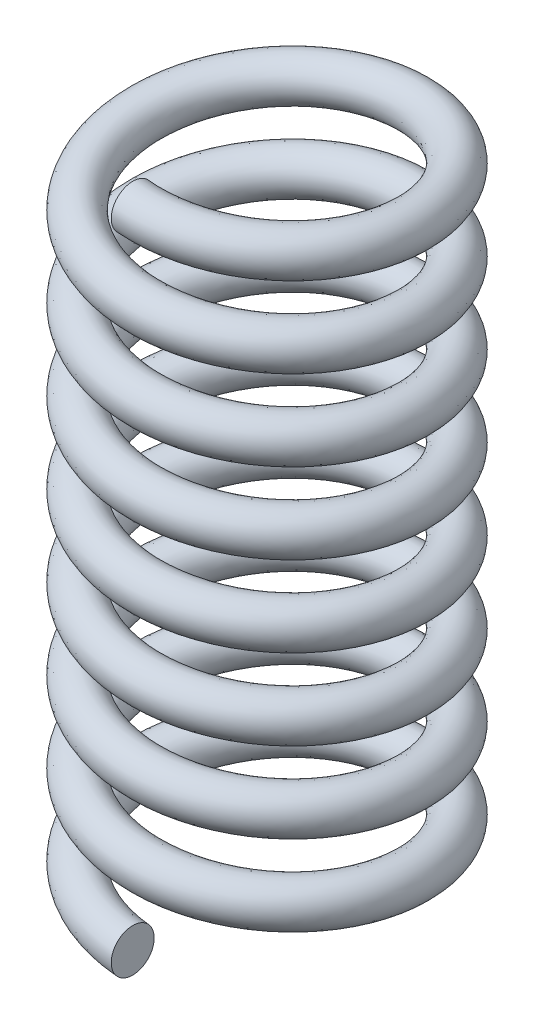
SolidWorks part; units mm, degrees
ref_plane "Front Plane" through (0, 0, 0) normal (0, 0, 1) x (1, 0, 0)
ref_plane "Top Plane" through (0, 0, 0) normal (0, 1, 0) x (1, 0, 0)
ref_plane "Right Plane" through (0, 0, 0) normal (1, 0, 0) x (0, 0, -1)
sketch "Sketch1" plane through (0, 0, 0) normal (0, 1, 0) x (1, 0, 0)
  circle A0 centre (0, 0) radius 25
  dimension "D1" = 50
curve "Helix/Spiral1" pitch 15 height 120 turns 8
sketch "Sketch2" plane through (0, 0, 0) normal (1, 0, 0) x (0, 0, -1)
  circle A0 centre (-25, 0) radius 4
  spline S0 degree 3 poles (-25, 0) (-25, 0.2252) (-24.3234, 0.6783) (-21.36, 1.3558) (-16.6856, 2.0339) (-10.6744, 2.7119) (-3.8082, 3.3898) (3.363, 4.0678) (10.2649, 4.7458) (16.3445, 5.4237) (21.1148, 6.1017) (24.1936, 6.7797) (25.3343, 7.4576) (24.4456, 8.1356) (21.5986, 8.8136) (17.0214, 9.4915) (11.0806, 10.1695) (4.2522, 10.8475) (-2.9168, 11.5254) (-9.8521, 12.2034) (-15.9983, 12.8814) (-20.8628, 13.5593) (-24.0561, 14.2373) (-25.3223, 14.9153) (-24.56, 15.5932) (-21.8303, 16.2712) (-17.3518, 16.9492) (-11.4833, 17.6271) (-4.6949, 18.3051) (2.4696, 18.9831) (9.4363, 19.661) (15.647, 20.339) (20.6043, 21.0169) (23.9111, 21.6949) (25.3024, 22.3729) (24.6668, 23.0508) (22.0552, 23.7288) (17.6768, 24.4068) (11.8824, 25.0847) (5.1361, 25.7627) (-2.0216, 26.4407) (-9.0174, 27.1186) (-15.2908, 27.7966) (-20.3393, 28.4746) (-23.7585, 29.1525) (-25.2745, 29.8305) (-24.7657, 30.5085) (-22.2731, 31.1864) (-17.9962, 31.8644) (-12.2777, 32.5424) (-5.5756, 33.2203) (1.5731, 33.8983) (8.5957, 34.5763) (14.9298, 35.2542) (20.068, 35.9322) (23.5985, 36.6102) (25.2386, 37.2881) (24.8569, 37.9661) (22.484, 38.6441) (18.31, 39.322) (12.6691, 40) (6.0135, 40.678) (-1.124, 41.3559) (-8.1713, 42.0339) (-14.5641, 42.7119) (-19.7902, 43.3898) (-23.431, 44.0678) (-25.1948, 44.7458) (-24.9402, 45.4237) (-22.6878, 46.1017) (-18.6179, 46.7797) (-13.0566, 47.4576) (-6.4494, 48.1356) (0.6745, 48.8136) (7.7444, 49.4915) (14.1938, 50.1695) (19.5063, 50.8475) (23.2561, 51.5254) (25.143, 52.2034) (25.0157, 52.8814) (22.8845, 53.5593) (18.92, 54.2373) (13.44, 54.9153) (6.8832, 55.5932) (-0.2249, 56.2712) (-7.315, 56.9492) (-13.8191, 57.6271) (-19.2162, 58.3051) (-23.0739, 58.9831) (-25.0833, 59.661) (-25.0833, 60.339) (-23.0739, 61.0169) (-19.2162, 61.6949) (-13.8191, 62.3729) (-7.315, 63.0508) (-0.2249, 63.7288) (6.8832, 64.4068) (13.44, 65.0847) (18.92, 65.7627) (22.8845, 66.4407) (25.0157, 67.1186) (25.143, 67.7966) (23.2561, 68.4746) (19.5063, 69.1525) (14.1938, 69.8305) (7.7444, 70.5085) (0.6745, 71.1864) (-6.4494, 71.8644) (-13.0566, 72.5424) (-18.6179, 73.2203) (-22.6878, 73.8983) (-24.9402, 74.5763) (-25.1948, 75.2542) (-23.431, 75.9322) (-19.7902, 76.6102) (-14.5641, 77.2881) (-8.1713, 77.9661) (-1.124, 78.6441) (6.0135, 79.322) (12.6691, 80) (18.31, 80.678) (22.484, 81.3559) (24.8569, 82.0339) (25.2386, 82.7119) (23.5985, 83.3898) (20.068, 84.0678) (14.9298, 84.7458) (8.5957, 85.4237) (1.5731, 86.1017) (-5.5756, 86.7797) (-12.2777, 87.4576) (-17.9962, 88.1356) (-22.2731, 88.8136) (-24.7657, 89.4915) (-25.2745, 90.1695) (-23.7585, 90.8475) (-20.3393, 91.5254) (-15.2908, 92.2034) (-9.0174, 92.8814) (-2.0216, 93.5593) (5.1361, 94.2373) (11.8824, 94.9153) (17.6768, 95.5932) (22.0552, 96.2712) (24.6668, 96.9492) (25.3024, 97.6271) (23.9111, 98.3051) (20.6043, 98.9831) (15.647, 99.661) (9.4363, 100.339) (2.4696, 101.0169) (-4.6949, 101.6949) (-11.4833, 102.3729) (-17.3518, 103.0508) (-21.8303, 103.7288) (-24.56, 104.4068) (-25.3223, 105.0847) (-24.0561, 105.7627) (-20.8628, 106.4407) (-15.9983, 107.1186) (-9.8521, 107.7966) (-2.9168, 108.4746) (4.2522, 109.1525) (11.0806, 109.8305) (17.0214, 110.5085) (21.5986, 111.1864) (24.4456, 111.8644) (25.3343, 112.5424) (24.1936, 113.2203) (21.1148, 113.8983) (16.3445, 114.5763) (10.2649, 115.2542) (3.363, 115.9322) (-3.8082, 116.6102) (-10.6744, 117.2881) (-16.6856, 117.9661) (-21.36, 118.6442) (-24.3234, 119.3217) (-25, 119.7748) (-25, 120) knots 0 0 0 0 0.00565 0.011299 0.016949 0.022599 0.028249 0.033898 0.039548 0.045198 0.050847 0.056497 0.062147 0.067797 0.073446 0.079096 0.084746 0.090395 0.096045 0.101695 0.107345 0.112994 0.118644 0.124294 0.129944 0.135593 0.141243 0.146893 0.152542 0.158192 0.163842 0.169492 0.175141 0.180791 0.186441 0.19209 0.19774 0.20339 0.20904 0.214689 0.220339 0.225989 0.231638 0.237288 0.242938 0.248588 0.254237 0.259887 0.265537 0.271186 0.276836 0.282486 0.288136 0.293785 0.299435 0.305085 0.310734 0.316384 0.322034 0.327684 0.333333 0.338983 0.344633 0.350282 0.355932 0.361582 0.367232 0.372881 0.378531 0.384181 0.389831 0.39548 0.40113 0.40678 0.412429 0.418079 0.423729 0.429379 0.435028 0.440678 0.446328 0.451977 0.457627 0.463277 0.468927 0.474576 0.480226 0.485876 0.491525 0.497175 0.502825 0.508475 0.514124 0.519774 0.525424 0.531073 0.536723 0.542373 0.548023 0.553672 0.559322 0.564972 0.570621 0.576271 0.581921 0.587571 0.59322 0.59887 0.60452 0.610169 0.615819 0.621469 0.627119 0.632768 0.638418 0.644068 0.649718 0.655367 0.661017 0.666667 0.672316 0.677966 0.683616 0.689266 0.694915 0.700565 0.706215 0.711864 0.717514 0.723164 0.728814 0.734463 0.740113 0.745763 0.751412 0.757062 0.762712 0.768362 0.774011 0.779661 0.785311 0.79096 0.79661 0.80226 0.80791 0.813559 0.819209 0.824859 0.830508 0.836158 0.841808 0.847458 0.853107 0.858757 0.864407 0.870056 0.875706 0.881356 0.887006 0.892655 0.898305 0.903955 0.909605 0.915254 0.920904 0.926554 0.932203 0.937853 0.943503 0.949153 0.954802 0.960452 0.966102 0.971751 0.977401 0.983051 0.988701 0.99435 1 1 1 1 construction
  dimension "D1" = 8
sweep "Sweep1" add profiles "Sketch2" path "Helix/Spiral1"
